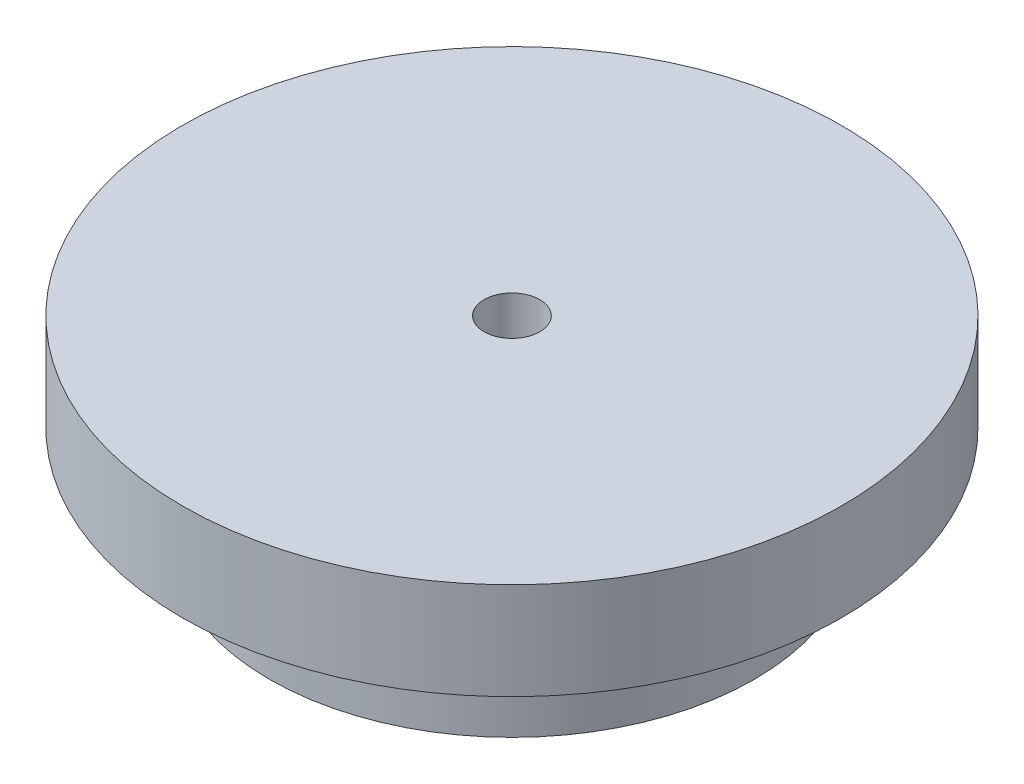
SolidWorks part; units mm, degrees
ref_plane "Front Plane" through (0, 0, 0) normal (0, 0, 1) x (1, 0, 0)
ref_plane "Top Plane" through (0, 0, 0) normal (0, 1, 0) x (1, 0, 0)
ref_plane "Right Plane" through (0, 0, 0) normal (1, 0, 0) x (0, 0, -1)
sketch "Sketch1" plane through (0, 0, 0) normal (0, 1, 0) x (1, 0, 0)
  line L39 (0, 8.5) -> (0, 11) construction
  line L40 (-1.5, 11) -> (1.5, 11)
  line L41 (-1.5, 11) -> (-2.4259, 8.1465)
  line L42 (1.5, 11) -> (2.4259, 8.1465)
  line L43 (6.7175, 8.8388) -> (4.045, 7.4758)
  line L44 (6.7175, 8.8388) -> (8.8388, 6.7175)
  line L45 (8.8388, 6.7175) -> (7.4758, 4.045)
  line L46 (11, 1.5) -> (8.1465, 2.4259)
  line L47 (11, 1.5) -> (11, -1.5)
  line L48 (11, -1.5) -> (8.1465, -2.4259)
  line L49 (8.8388, -6.7175) -> (7.4758, -4.045)
  line L50 (8.8388, -6.7175) -> (6.7175, -8.8388)
  line L51 (6.7175, -8.8388) -> (4.045, -7.4758)
  line L52 (1.5, -11) -> (2.4259, -8.1465)
  line L53 (1.5, -11) -> (-1.5, -11)
  line L54 (-1.5, -11) -> (-2.4259, -8.1465)
  line L55 (-6.7175, -8.8388) -> (-4.045, -7.4758)
  line L56 (-6.7175, -8.8388) -> (-8.8388, -6.7175)
  line L57 (-8.8388, -6.7175) -> (-7.4758, -4.045)
  line L58 (-11, -1.5) -> (-8.1465, -2.4259)
  line L59 (-11, -1.5) -> (-11, 1.5)
  line L60 (-11, 1.5) -> (-8.1465, 2.4259)
  line L61 (-8.8388, 6.7175) -> (-7.4758, 4.045)
  line L62 (-8.8388, 6.7175) -> (-6.7175, 8.8388)
  line L63 (-6.7175, 8.8388) -> (-4.045, 7.4758)
  circle A14 centre (0, 0) radius 8.5 construction
  arc A15 (2.4259, 8.1465) -> (4.045, 7.4758) centre (0, 0) cw
  arc A16 (7.4758, 4.045) -> (8.1465, 2.4259) centre (0, 0) cw
  arc A17 (8.1465, -2.4259) -> (7.4758, -4.045) centre (0, 0) cw
  arc A18 (4.045, -7.4758) -> (2.4259, -8.1465) centre (0, 0) cw
  arc A19 (-2.4259, -8.1465) -> (-4.045, -7.4758) centre (0, 0) cw
  arc A20 (-7.4758, -4.045) -> (-8.1465, -2.4259) centre (0, 0) cw
  arc A21 (-8.1465, 2.4259) -> (-7.4758, 4.045) centre (0, 0) cw
  arc A22 (-4.045, 7.4758) -> (-2.4259, 8.1465) centre (0, 0) cw
  circle A23 centre (0, 0) radius 25
  point P31 (0, 0)
  point P71 (0, 11)
  point P105 (0, 0)
  dimension "D1" = 50
  dimension "D5" = 17
  dimension "D6" = 2.5
  dimension "D7" = 3
  dimension "D8" = 3
  dimension "D9" = 8
extrude "Boss-Extrude1" add sketch "Sketch1" along normal blind 10
sketch "Sketch2" plane through (0, 10, 0) normal (0, 1, 0) x (1, 0, 0)
  circle A0 centre (0, 0) radius 2.875
  circle A1 centre (0, 0) radius 34
  dimension "D1" = 5.75
  dimension "D2" = 68
extrude "Boss-Extrude2" add sketch "Sketch2" along normal blind 10
